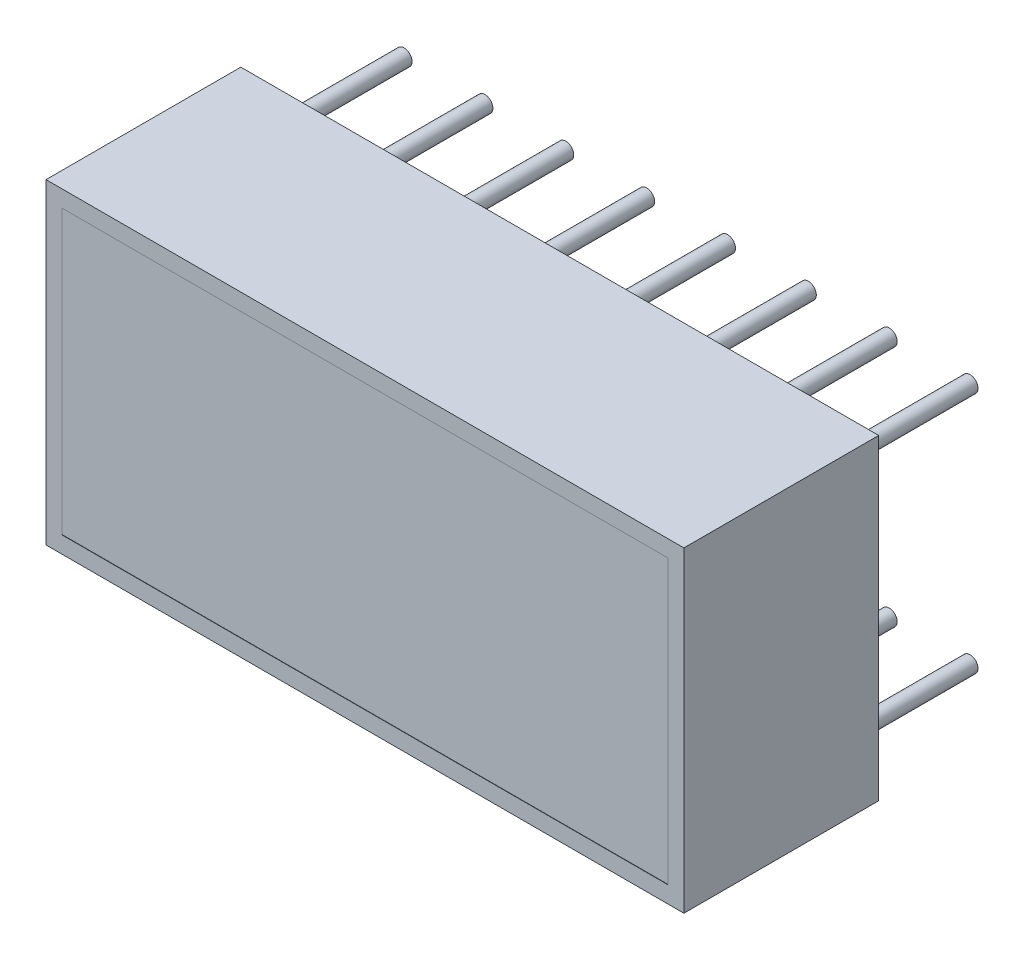
SolidWorks part; units mm, degrees
ref_plane "Спереди" through (0, 0, 0) normal (0, 0, 1) x (1, 0, 0)
ref_plane "Сверху" through (0, 0, 0) normal (0, 1, 0) x (1, 0, 0)
ref_plane "Справа" through (0, 0, 0) normal (1, 0, 0) x (0, 0, -1)
sketch "Эскиз1" plane through (0, 0, 0) normal (0, 0, 1) x (1, 0, 0)
  line L1 (-10.02, -4.97) -> (10.02, -4.97)
  line L2 (-10.02, -4.97) -> (-10.02, 4.97)
  line L3 (-10.02, 4.97) -> (10.02, 4.97)
  line L4 (10.02, -4.97) -> (10.02, 4.97)
  line L5 (-10.02, -4.97) -> (10.02, 4.97) construction
  line L6 (-10.02, 4.97) -> (10.02, -4.97) construction
  point P0 (0, 0)
  dimension "D1" = 20.04
  dimension "D2" = 9.94
extrude "Бобышка-Вытянуть1" add sketch "Эскиз1" along normal blind 6.12
sketch "Эскиз2" plane through (0, 0, 0) normal (0, 0, -1) x (-1, 0, 0)
  circle A0 centre (8.89, -3.81) radius 0.25
  dimension "D3" = 0.5
  dimension "D1" = 3.81
  dimension "D2" = 8.89
extrude "Бобышка-Вытянуть2" add sketch "Эскиз2" along normal blind 4
pattern_linear "Линейный массив1" count 8 spacing 2.54 along (1, 0, 0) count 2 spacing 7.62 along (0, 1, 0) of "Бобышка-Вытянуть2"
sketch "Эскиз3" plane through (0, 0, 6.12) normal (0, 0, 1) x (1, 0, 0)
  line L1 (9.525, 4.445) -> (-9.525, 4.445)
  line L2 (9.525, 4.445) -> (9.525, -4.445)
  line L3 (9.525, -4.445) -> (-9.525, -4.445)
  line L4 (-9.525, 4.445) -> (-9.525, -4.445)
  line L5 (9.525, 4.445) -> (-9.525, -4.445) construction
  line L6 (9.525, -4.445) -> (-9.525, 4.445) construction
  point P0 (0, 0)
  dimension "D1" = 19.05
  dimension "D2" = 8.89
extrude "Вырез-Вытянуть1" cut sketch "Эскиз3" against normal blind 0.01
